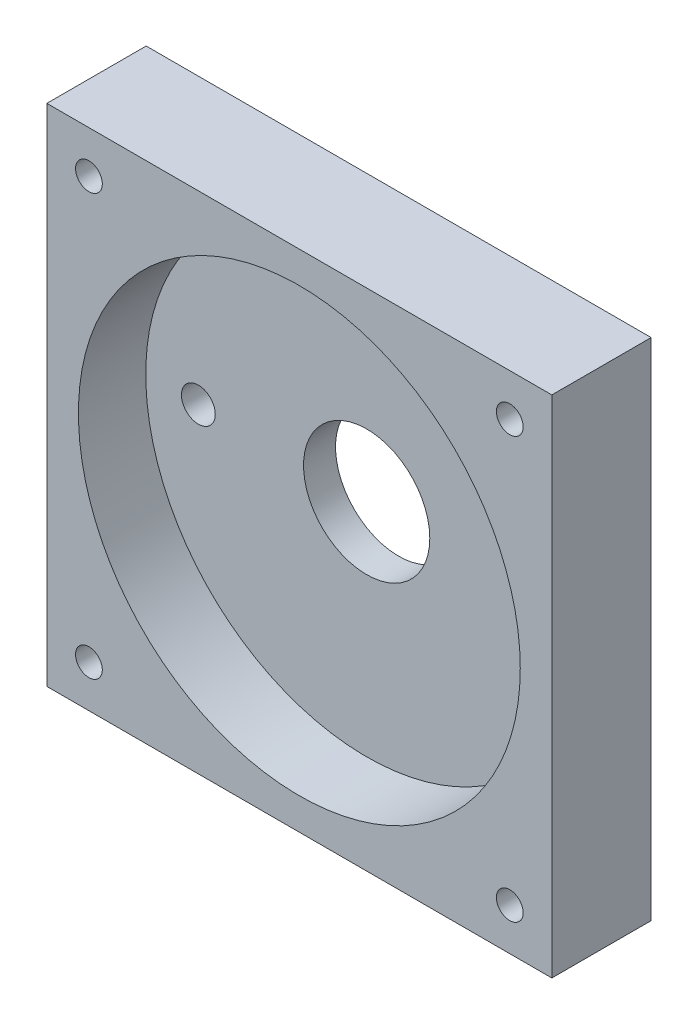
SolidWorks part; units mm, degrees
ref_plane "Front Plane" through (0, 0, 0) normal (0, 0, 1) x (1, 0, 0)
ref_plane "Top Plane" through (0, 0, 0) normal (0, 1, 0) x (1, 0, 0)
ref_plane "Right Plane" through (0, 0, 0) normal (1, 0, 0) x (0, 0, -1)
sketch "Sketch1" plane through (0, 0, 0) normal (0, 0, 1) x (1, 0, 0)
  line L1 (-38.1, -38.1) -> (38.1, -38.1)
  line L2 (-38.1, -38.1) -> (-38.1, 38.1)
  line L3 (-38.1, 38.1) -> (38.1, 38.1)
  line L4 (38.1, -38.1) -> (38.1, 38.1)
  line L5 (-38.1, -38.1) -> (38.1, 38.1) construction
  line L6 (-38.1, 38.1) -> (38.1, -38.1) construction
  point P0 (0, 0)
  dimension "D1" = 76.2
  dimension "D2" = 76.2
extrude "Boss-Extrude1" add sketch "Sketch1" along normal blind 12.7
sketch "Sketch2" plane through (0, 0, 12.7) normal (0, 0, 1) x (1, 0, 0)
  circle A0 centre (0, 0) radius 33.3375
extrude "Cut-Extrude1" cut sketch "Sketch2" against normal blind 10.16
sketch "Sketch3" plane through (0, 0, 2.54) normal (0, 0, 1) x (1, 0, 0)
  circle A0 centre (0, 0) radius 9.525
  dimension "D1" = 19.05
extrude "Cut-Extrude2" cut sketch "Sketch3" against normal blind 19.05
sketch "Sketch4" plane through (0, 0, 2.54) normal (0, 0, 1) x (1, 0, 0)
  line L0 (-25.4, 0) -> (25.4, 0) construction
  line L2 (-31.75, -31.75) -> (31.75, -31.75) construction
  line L3 (-31.75, -31.75) -> (-31.75, 31.75) construction
  line L4 (-31.75, 31.75) -> (31.75, 31.75) construction
  line L5 (31.75, -31.75) -> (31.75, 31.75) construction
  line L6 (-31.75, -31.75) -> (31.75, 31.75) construction
  line L7 (-31.75, 31.75) -> (31.75, -31.75) construction
  circle A0 centre (-31.75, 31.75) radius 1.27
  circle A1 centre (31.75, 31.75) radius 1.27
  circle A2 centre (31.75, -31.75) radius 1.27
  circle A3 centre (-31.75, -31.75) radius 1.27
  circle A4 centre (-25.4, 0) radius 2.5527
  circle A5 centre (25.4, 0) radius 2.5527
  point P0 (0, 0)
  point P5 (0, 0)
  dimension "D1" = 50.8
  dimension "D4" = 2.54
  dimension "D5" = 5.1054
  dimension "D2" = 63.5
  dimension "D3" = 63.5
extrude "Cut-Extrude3" cut sketch "Sketch4" against normal through all and the other way through all
hole_wizard "#10-32 Tapped Hole1" positions "Sketch6" profile "Sketch5" tap size "#10-32" standard "ANSI Inch" end condition through all
sketch "Sketch6" plane through (0, 0, 12.7) normal (0, 0, 1) x (1, 0, 0)
  point P0 (-31.75, 31.75)
  point P3 (-31.75, -31.75)
  point P6 (31.75, -31.75)
  point P9 (31.75, 31.75)
sketch "Sketch5" plane through (-31.75, 31.75, 12.7) normal (1, 0, 0) x (0, -1, 0)
  line L0 (0, 0) -> (0, 12.7)
  line L1 (0, 12.7) -> (2.0193, 12.7)
  line L2 (2.0193, 12.7) -> (2.0193, 0)
  line L5 (2.0193, 0) -> (0, 0)
  line L11 (0, -6.35) -> (0, 107.95) construction
  dimension "Thread Major Dia." = 4.0386
  dimension "Thru Tap Drill Depth" = 12.7
sketch "Sketch7" plane through (0, 0, 0) normal (0, 0, -1) x (-1, 0, 0)
  line L0 (38.1, 38.1) -> (38.1, -38.1) construction
  line L1 (38.1, -38.1) -> (-38.1, -38.1) construction
  line L2 (-38.1, -38.1) -> (-38.1, 38.1) construction
  line L3 (-38.1, 38.1) -> (38.1, 38.1) construction
  line L4 (38.1, 38.1) -> (38.1, -38.1)
  line L5 (38.1, -38.1) -> (-38.1, -38.1)
  line L6 (-38.1, -38.1) -> (-38.1, 38.1)
  line L7 (-38.1, 38.1) -> (38.1, 38.1)
  circle A0 centre (-25.4, 0) radius 2.5527 construction
  circle A1 centre (-31.75, 31.75) radius 2.0193 construction
  circle A2 centre (0, 0) radius 9.525 construction
  circle A3 centre (25.4, 0) radius 2.5527 construction
  circle A4 centre (31.75, 31.75) radius 2.0193 construction
  circle A5 centre (31.75, -31.75) radius 2.0193 construction
  circle A6 centre (-25.4, 0) radius 2.5527
  circle A7 centre (-31.75, 31.75) radius 2.0193
  circle A8 centre (0, 0) radius 9.525
  circle A9 centre (25.4, 0) radius 2.5527
  circle A10 centre (31.75, 31.75) radius 2.0193
  circle A11 centre (31.75, -31.75) radius 2.0193
  circle A12 centre (-31.75, -31.75) radius 2.0193 construction
  circle A13 centre (-31.75, -31.75) radius 2.0193
extrude "Boss-Extrude2" add sketch "Sketch7" along normal blind 2.286
